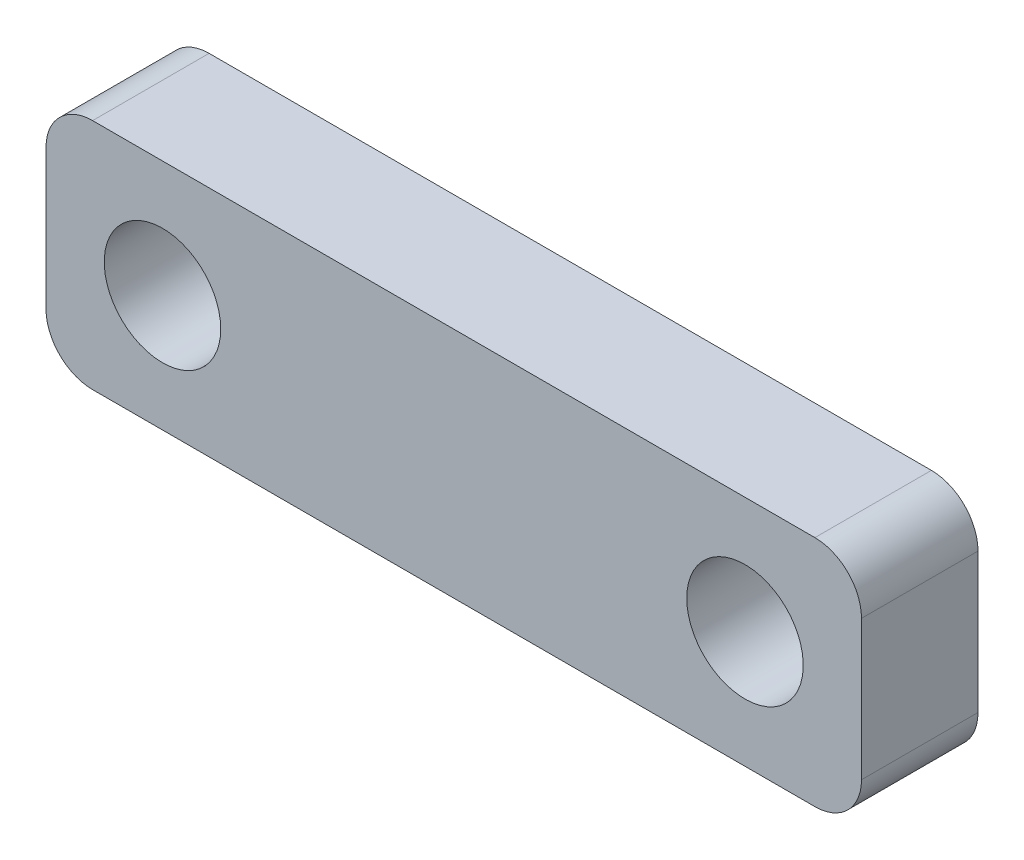
SolidWorks part; units mm, degrees
ref_plane "Plan de face" through (0, 0, 0) normal (0, 0, 1) x (1, 0, 0)
ref_plane "Plan de dessus" through (0, 0, 0) normal (0, 1, 0) x (1, 0, 0)
ref_plane "Plan de droite" through (0, 0, 0) normal (1, 0, 0) x (0, 0, -1)
sketch "Esquisse1" plane through (0, 0, 0) normal (0, 0, 1) x (1, 0, 0)
  line L0 (-16.3416, 3.3696) -> (18.6584, 3.3696) construction
  line L1 (-16.3416, 8.3696) -> (18.6584, 8.3696)
  line L2 (-16.3416, 8.3696) -> (-16.3416, -1.6304)
  line L3 (-16.3416, -1.6304) -> (18.6584, -1.6304)
  line L4 (18.6584, 8.3696) -> (18.6584, -1.6304)
  line L5 (-16.3416, 3.3696) -> (-11.3416, 3.3696) construction
  line L6 (1.1584, 8.3696) -> (1.1584, -1.6304) construction
  circle A0 centre (-11.3416, 3.3696) radius 2.5
  circle A1 centre (13.6584, 3.3696) radius 2.5
  dimension "D1" = 35
  dimension "D2" = 10
  dimension "D3" = 5
extrude "Boss.-Extru.1" add sketch "Esquisse1" along normal blind 5
fillet "Congé1" radius 2 1 edges at (-16.3416, 8.3696, 2.5)
fillet "Congé2" radius 2 1 edges at (-16.3416, -1.6304, 2.5)
fillet "Congé3" radius 2 1 edges at (18.6584, 8.3696, 2.5)
fillet "Congé4" radius 2 1 edges at (18.6584, -1.6304, 2.5)
